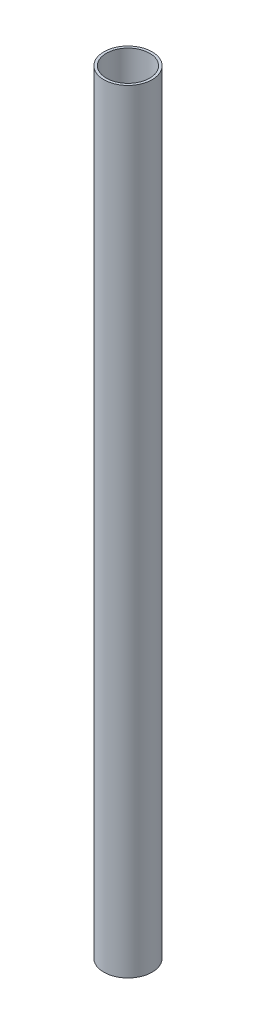
SolidWorks part; units mm, degrees
material "6061-T6 (SS)"
ref_plane "Front Plane" through (0, 0, 0) normal (0, 0, 1) x (1, 0, 0)
ref_plane "Top Plane" through (0, 0, 0) normal (0, 1, 0) x (1, 0, 0)
ref_plane "Right Plane" through (0, 0, 0) normal (1, 0, 0) x (0, 0, -1)
sketch3d "3DSketch1"
  line L0 (0, 0, 0) -> (0, 508, 0)
  line L1 (-215, 508, 0) -> (215, 508, 0)
  point P5 (0, 508, 0)
  dimension "D1" = 508
  dimension "D2" = 430
other "Al round tubing AL RND TUBE 1.25 OD X 0.063 WALL(1)"
ref_plane "Plane1" through (0, 0, 0) normal (0, 1, 0) x (1, 0, 0)
sketch "Sketch130" plane through (0, 0, 0) normal (0, 1, 0) x (1, 0, 0)
  circle A0 centre (0, 0) radius 14.224
  circle A1 centre (0, 0) radius 15.875
  point P3 (0, 0)
  dimension "In_dia" = 28.448
  dimension "Out_dia" = 31.75
sketch "Sketch117" plane through (0, 508, 0) normal (0, 1, 0) x (1, 0, 0)
  circle A0 centre (0, 0) radius 14.224 construction
  circle A1 centre (0, 0) radius 14.224
ref_plane "Plane2" through (0, 590, 0) normal (0, 1, 0) x (1, 0, 0)
sketch "Sketch119" plane through (0, 590, 0) normal (0, 1, 0) x (1, 0, 0)
  line L0 (-11, 0) -> (11, 0) construction
  line L1 (-11, 11) -> (11, 11)
  line L2 (-11, -11) -> (11, -11)
  arc A0 (-11, 11) -> (-11, -11) centre (-11, 0) ccw
  arc A1 (11, -11) -> (11, 11) centre (11, 0) ccw
  point P2 (0, 0)
  dimension "D1" = 22
  dimension "D2" = 11
sketch "Sketch120" plane through (0, 0, 0) normal (0, 0, 1) x (1, 0, 0)
  line L9 (0, 590) -> (0, 508) construction
  line L11 (-22, 590) -> (-20, 508)
  line L12 (14.224, 508) -> (-14.224, 508) construction
  line L13 (-11, 590) -> (11, 590) construction
  line L14 (22, 590) -> (20, 508)
  dimension "D1" = 20
  dimension "D2" = 22
sketch3d "3DSketch5"
  line L0 (38.7646, 590, 0) -> (-38.7646, 590, 0)
  point P0 (0, 0, 0)
  point P4 (0, 0, 0)
  dimension "D1" = 77.5293
sketch3d "3DSketch7"
  point P4 (0, 0, 0)
